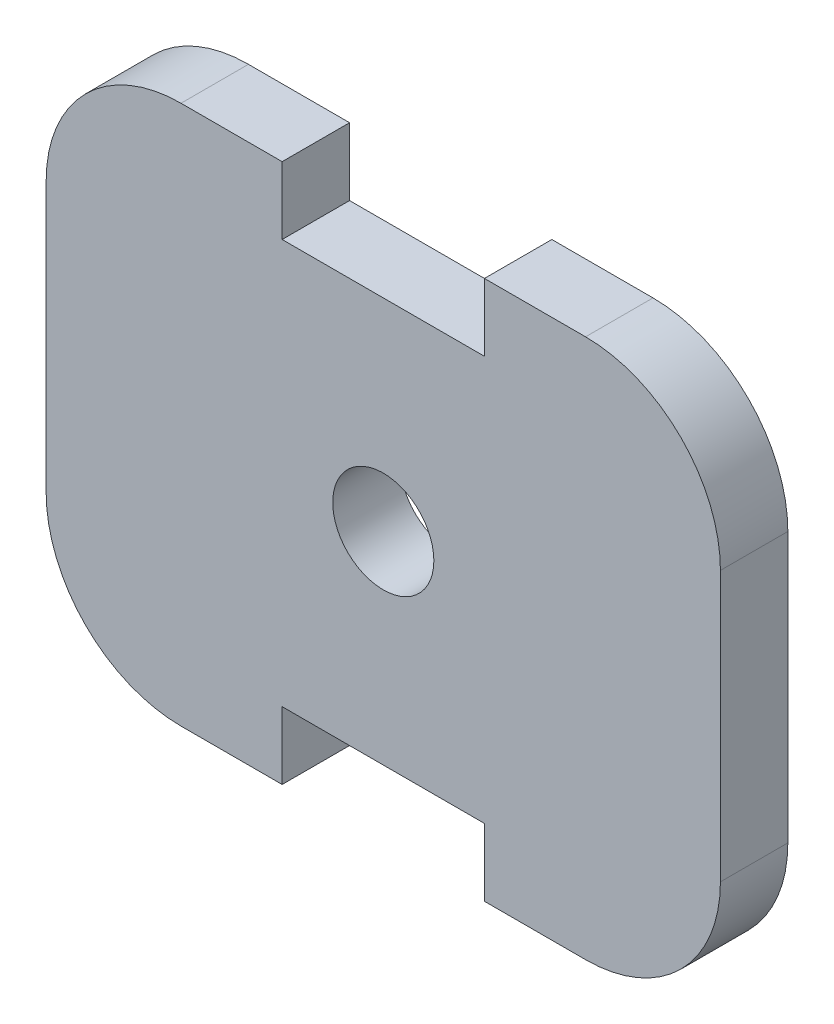
SolidWorks part; units mm, degrees
ref_plane "Front Plane" through (0, 0, 0) normal (0, 0, 1) x (1, 0, 0)
ref_plane "Top Plane" through (0, 0, 0) normal (0, 1, 0) x (1, 0, 0)
ref_plane "Right Plane" through (0, 0, 0) normal (1, 0, 0) x (0, 0, -1)
sketch "Sketch1" plane through (0, 0, 0) normal (0, 0, 1) x (1, 0, 0)
  line L0 (1.5875, 21.137) -> (-3.175, 21.137)
  line L1 (15.875, -4.263) -> (11.1125, -4.263)
  line L2 (22.225, 2.087) -> (22.225, 14.787)
  line L3 (15.875, 21.137) -> (11.1125, 21.137)
  line L4 (-9.525, 2.087) -> (-9.525, 14.787)
  line L5 (22.225, -4.263) -> (-9.525, 21.137) construction
  line L6 (22.225, 21.137) -> (-9.525, -4.263) construction
  line L7 (1.5875, -4.263) -> (-3.175, -4.263)
  line L8 (1.5875, 21.137) -> (1.5875, 17.962)
  line L9 (1.5875, 17.962) -> (11.1125, 17.962)
  line L10 (11.1125, 21.137) -> (11.1125, 17.962)
  line L12 (1.5875, -4.263) -> (1.5875, -1.088)
  line L13 (1.5875, -1.088) -> (11.1125, -1.088)
  line L14 (11.1125, -4.263) -> (11.1125, -1.088)
  circle A0 centre (6.35, 8.437) radius 2.3813
  arc A1 (-3.175, -4.263) -> (-9.525, 2.087) centre (-3.175, 2.087) cw
  arc A2 (15.875, -4.263) -> (22.225, 2.087) centre (15.875, 2.087) ccw
  arc A3 (22.225, 14.787) -> (15.875, 21.137) centre (15.875, 14.787) ccw
  arc A4 (-3.175, 21.137) -> (-9.525, 14.787) centre (-3.175, 14.787) ccw
  dimension "D3" = 6.35
  dimension "D1" = 25.4
  dimension "D2" = 31.75
  dimension "D4" = 3.175
  dimension "D5" = 3.175
  dimension "D6" = 9.525
  dimension "D7" = 9.525
  dimension "D8" = 11.1125
  dimension "D9" = 11.1125
extrude "Boss-Extrude1" add sketch "Sketch1" along normal blind 3.175 contours L0 A4 L4 A1 L7 L12 L13 L14 L1 A2 L2 A3 L3 L10 L9 L8
